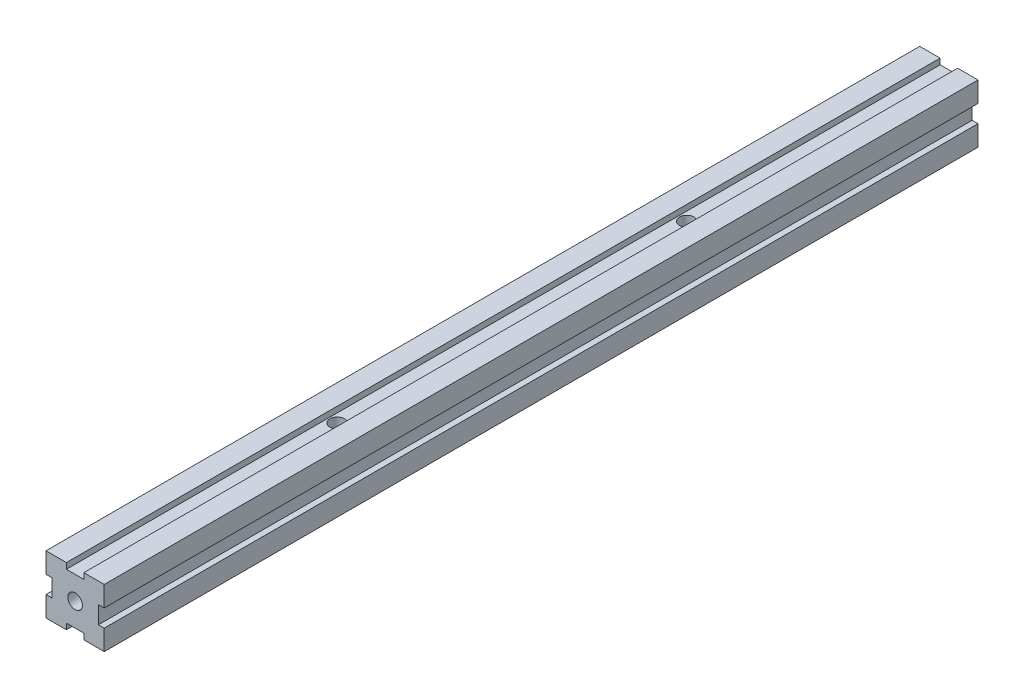
SolidWorks part; units mm, degrees
ref_plane "前视基准面" through (0, 0, 0) normal (0, 0, 1) x (1, 0, 0)
ref_plane "上视基准面" through (0, 0, 0) normal (0, 1, 0) x (1, 0, 0)
ref_plane "右视基准面" through (0, 0, 0) normal (1, 0, 0) x (0, 0, -1)
sketch "草图1" plane through (0, 0, 0) normal (0, 0, 1) x (1, 0, 0)
  line L0 (0, -13) -> (0, -20)
  line L1 (0, 0) -> (7, 0)
  line L2 (0, 0) -> (0, -7)
  line L3 (0, -20) -> (7, -20)
  line L4 (20, 0) -> (20, -7)
  line L5 (20, -7) -> (18, -7)
  line L6 (13, -20) -> (20, -20)
  line L7 (20, -13) -> (18, -13)
  line L8 (18, -7) -> (18, -13)
  line L9 (0, -7) -> (2, -7)
  line L10 (13, 0) -> (20, 0)
  line L11 (0, -13) -> (2, -13)
  line L12 (2, -7) -> (2, -13)
  line L13 (20, -13) -> (20, -20)
  line L14 (7, 0) -> (7, -2)
  line L15 (7, -2) -> (13, -2)
  line L16 (13, 0) -> (13, -2)
  line L17 (0, -7) -> (0, -13) construction
  line L18 (7, -20) -> (7, -18)
  line L19 (7, -18) -> (13, -18)
  line L20 (13, -20) -> (13, -18)
  line L21 (7, 0) -> (13, 0) construction
  line L22 (20, -7) -> (20, -13) construction
  line L23 (13, -20) -> (7, -20) construction
  line L24 (2, -10) -> (18, -10) construction
  line L25 (10, -2) -> (10, -18) construction
  circle A0 centre (10, -10) radius 2.5
  point P21 (10, 0)
  point P22 (10, -2)
  point P23 (10, -18)
  point P24 (2, -10)
  point P25 (18, -10)
  point P26 (0, -10)
  dimension "D13" = 5
  dimension "D1" = 20
  dimension "D2" = 20
  dimension "D3" = 6
  dimension "D4" = 6
  dimension "D5" = 6
  dimension "D6" = 6
  dimension "D7" = 10
  dimension "D8" = 10
  dimension "D9" = 2
  dimension "D10" = 2
  dimension "D11" = 2
  dimension "D12" = 2
extrude "凸台-拉伸1" add sketch "草图1" along normal blind 300
sketch "草图2" plane through (0, 0, 0) normal (0, 1, 0) x (1, 0, 0)
  line L0 (10, -300) -> (10, 0) construction
  line L3 (13, -300) -> (7, -300) construction
  line L4 (13, 0) -> (7, 0) construction
  line L5 (0, -150) -> (20, -150) construction
  line L6 (0, -300) -> (0, 0) construction
  line L7 (20, -300) -> (20, 0) construction
  line L8 (10, -90) -> (10, -210) construction
  circle A0 centre (10, -90) radius 2.5
  circle A1 centre (10, -210) radius 2.5
  point P16 (10, -150)
  dimension "D1" = 5
  dimension "D2" = 120
extrude "切除-拉伸1" cut sketch "草图2" against normal through all
